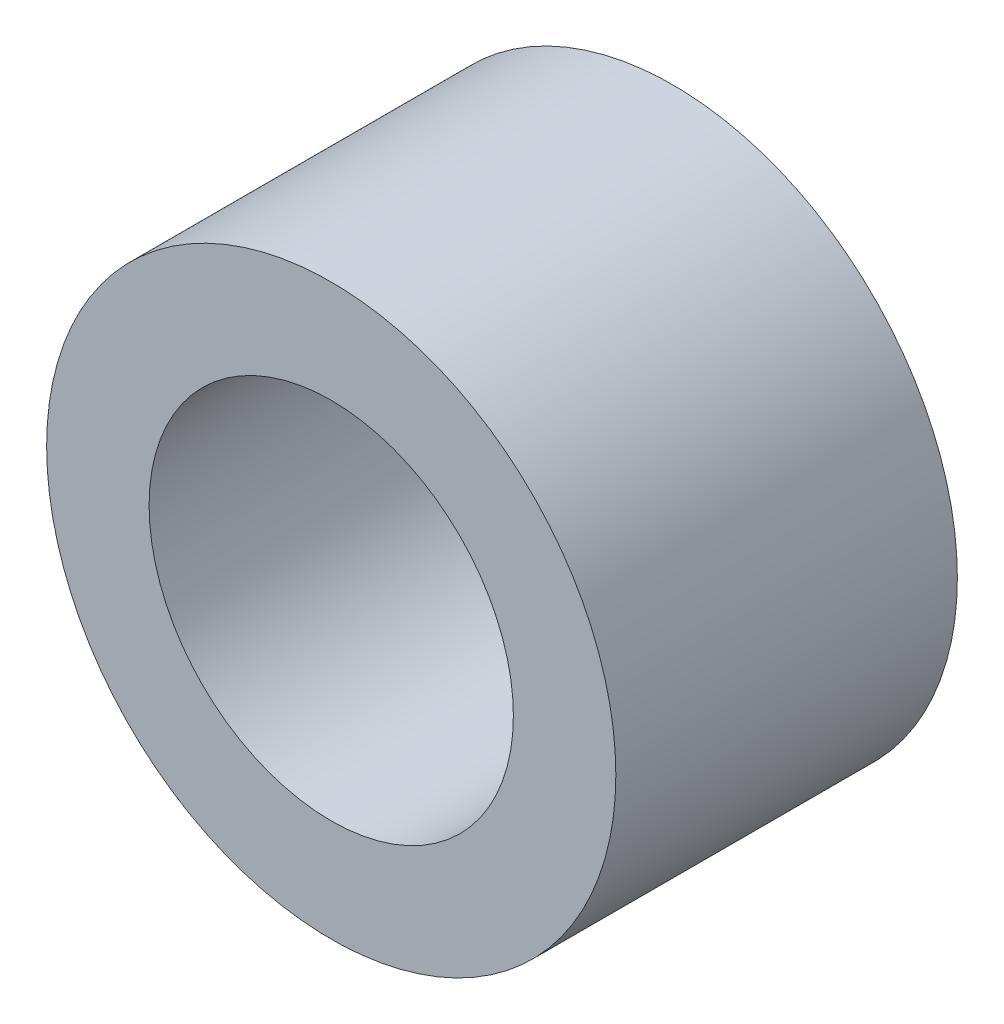
SolidWorks part; units mm, degrees
material "ABS"
ref_plane "Front" through (0, 0, 0) normal (0, 0, 1) x (1, 0, 0)
ref_plane "Top" through (0, 0, 0) normal (0, 1, 0) x (1, 0, 0)
ref_plane "Right" through (0, 0, 0) normal (1, 0, 0) x (0, 0, -1)
sketch "Эскиз1" plane through (0, 0, 0) normal (0, 0, 1) x (1, 0, 0)
  circle A0 centre (0, 0) radius 1.6
  circle A1 centre (0, 0) radius 2.5
  dimension "D1" = 3.2
  dimension "D2" = 5
extrude "Бобышка-Вытянуть1" add sketch "Эскиз1" along normal blind 3
